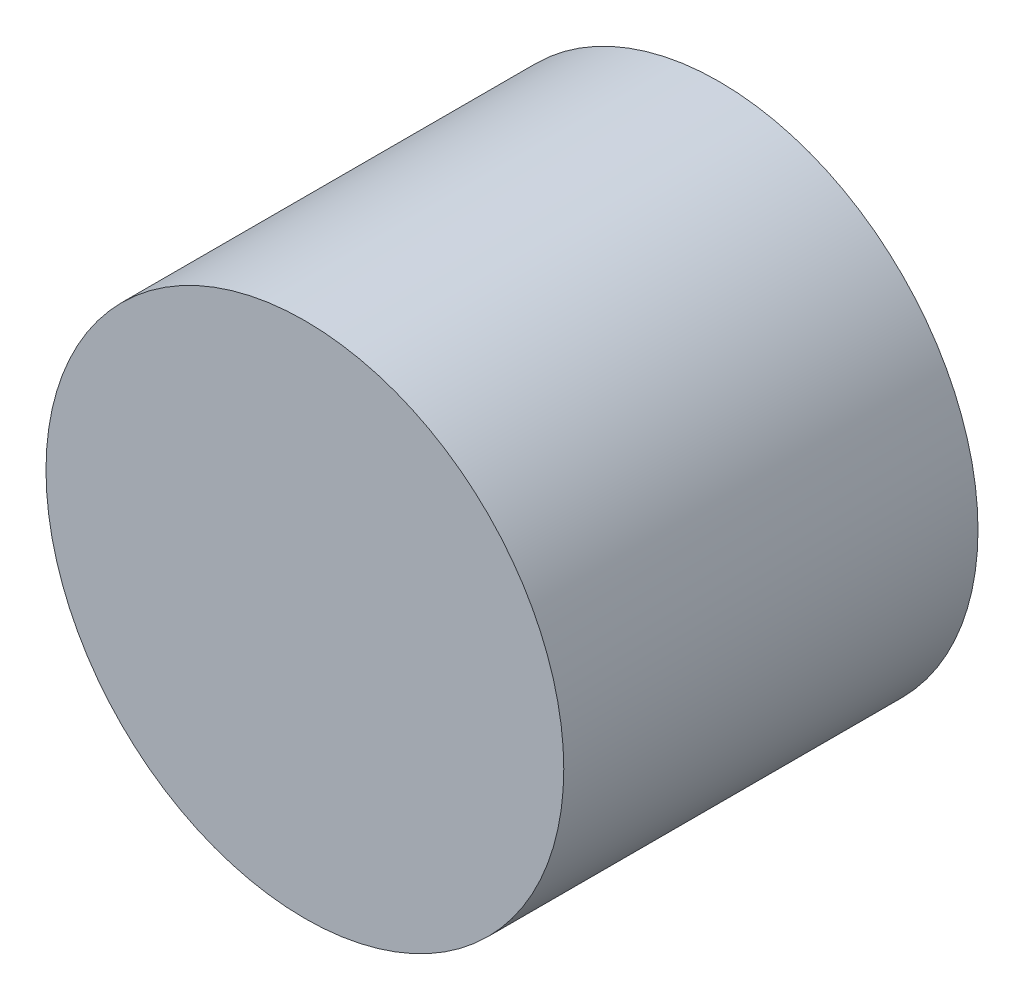
SolidWorks part; units mm, degrees
ref_plane "Front Plane" through (0, 0, 0) normal (0, 0, 1) x (1, 0, 0)
ref_plane "Top Plane" through (0, 0, 0) normal (0, 1, 0) x (1, 0, 0)
ref_plane "Right Plane" through (0, 0, 0) normal (1, 0, 0) x (0, 0, -1)
sketch "Sketch1" plane through (0, 0, 0) normal (0, 0, 1) x (1, 0, 0)
  circle A0 centre (0, 0) radius 15.875
  dimension "D1" = 31.75
extrude "Boss-Extrude1" add sketch "Sketch1" along normal blind 25.4
sketch "Sketch2" plane through (0, 0, 25.4) normal (0, 0, 1) x (1, 0, 0)
  point P0 (0, 0)
